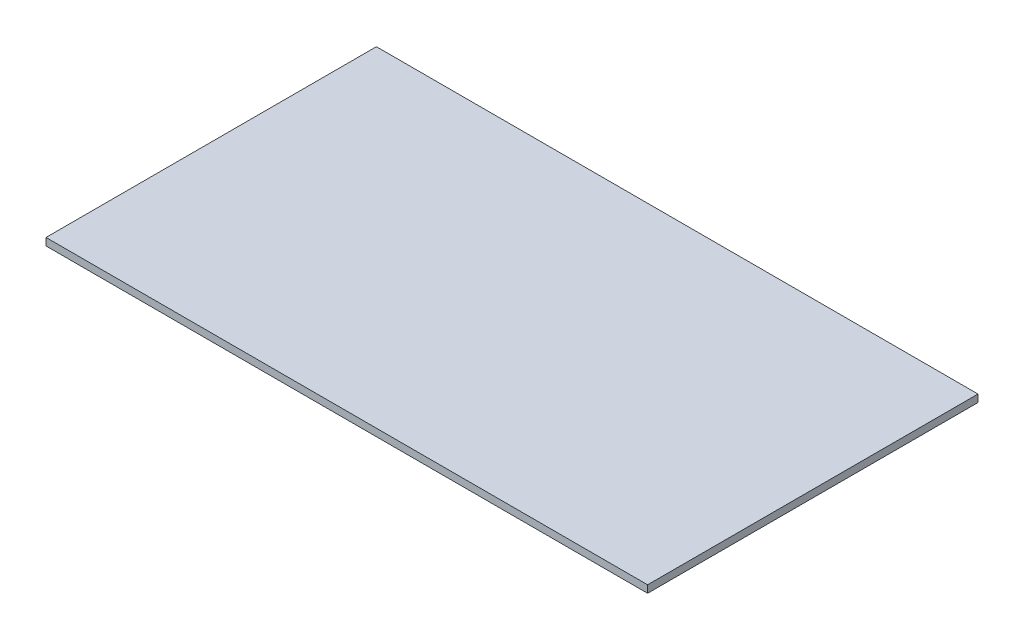
SolidWorks part; units mm, degrees
ref_plane "Front Plane" through (0, 0, 0) normal (0, 0, 1) x (1, 0, 0)
ref_plane "Top Plane" through (0, 0, 0) normal (0, 1, 0) x (1, 0, 0)
ref_plane "Right Plane" through (0, 0, 0) normal (1, 0, 0) x (0, 0, -1)
sketch "Sketch1" plane through (0, 0, 0) normal (0, 1, 0) x (1, 0, 0)
  line L1 (122, -67) -> (-122, -67)
  line L2 (122, -67) -> (122, 67)
  line L3 (122, 67) -> (-122, 67)
  line L4 (-122, -67) -> (-122, 67)
  line L5 (122, -67) -> (-122, 67) construction
  line L6 (122, 67) -> (-122, -67) construction
  point P0 (0, 0)
  dimension "D1" = 244
  dimension "D2" = 134
extrude "Boss-Extrude1" add sketch "Sketch1" along normal blind 3
